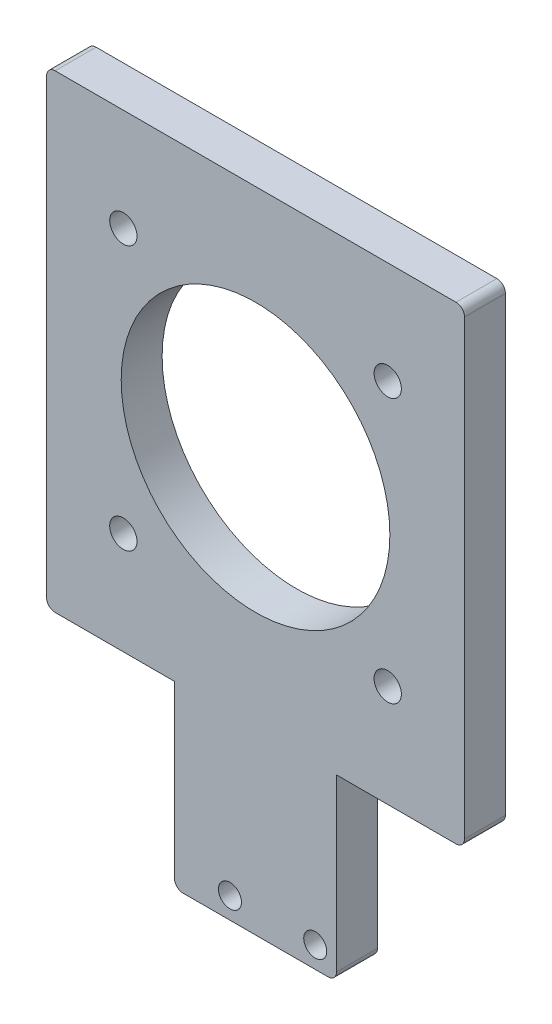
SolidWorks part; units mm, degrees
ref_plane "Plan de face" through (0, 0, 0) normal (0, 0, 1) x (1, 0, 0)
ref_plane "Plan de dessus" through (0, 0, 0) normal (0, 1, 0) x (1, 0, 0)
ref_plane "Plan de droite" through (0, 0, 0) normal (1, 0, 0) x (0, 0, -1)
ref_plane "Plan1" through (0, 0, 0) normal (0, 0, -1) x (-1, 0, 0)
sketch "Esquisse1" plane through (0, 0, 0) normal (0, 0, -1) x (-1, 0, 0)
  line L0 (-12.0004, 3.6502) -> (-12.0004, 56.6502)
  line L5 (-13.0004, 57.6502) -> (-60.0004, 57.6502)
  line L11 (-61.0004, 56.6502) -> (-61.0004, 3.6502)
  line L15 (-60.0004, 2.6502) -> (-46.0004, 2.6502)
  line L16 (-46.0004, 2.6502) -> (-46.0004, -17.3498)
  line L21 (-45.0004, -18.3498) -> (-28.0004, -18.3498)
  line L26 (-27.0004, -17.3498) -> (-27.0004, 2.6502)
  line L27 (-27.0004, 2.6502) -> (-13.0004, 2.6502)
  circle A0 centre (-36.5004, 30.1502) radius 15.75
  circle A1 centre (-52.0004, 14.6502) radius 1.6
  circle A2 centre (-52.0004, 45.6502) radius 1.6
  circle A3 centre (-21.0004, 14.6502) radius 1.6
  circle A4 centre (-21.0004, 45.6502) radius 1.6
  arc A5 (-61.0004, 56.6502) -> (-60.0004, 57.6502) centre (-60.0004, 56.6502) cw
  arc A6 (-13.0004, 57.6502) -> (-12.0004, 56.6502) centre (-13.0004, 56.6502) cw
  arc A7 (-61.0004, 3.6502) -> (-60.0004, 2.6502) centre (-60.0004, 3.6502) ccw
  arc A8 (-46.0004, -17.3498) -> (-45.0004, -18.3498) centre (-45.0004, -17.3498) ccw
  arc A9 (-28.0004, -18.3498) -> (-27.0004, -17.3498) centre (-28.0004, -17.3498) ccw
  arc A10 (-13.0004, 2.6502) -> (-12.0004, 3.6502) centre (-13.0004, 3.6502) ccw
  circle A11 centre (-43.5004, -15.8498) radius 1.35
  circle A12 centre (-33.5004, -15.8498) radius 1.35
  dimension "D1" = 31.5
  dimension "D2" = 36.5004
  dimension "D3" = 30.1502
  dimension "D4" = 15.5
  dimension "D5" = 15.5
  dimension "D6" = 3.2
  dimension "D7" = 15.5
  dimension "D8" = 15.5
  dimension "D9" = 3.2
  dimension "D10" = 3.2
  dimension "D11" = 15.5
  dimension "D12" = 15.5
  dimension "D13" = 3.2
  dimension "D14" = 15.5
  dimension "D15" = 15.5
  dimension "D23" = 1
  dimension "D24" = 1
  dimension "D25" = 1
  dimension "D26" = 1
  dimension "D27" = 1
  dimension "D28" = 1
  dimension "D29" = 2.7
  dimension "D30" = 2.7
  dimension "D31" = 10
  dimension "D32" = 2.5
  dimension "D33" = 2.5
  dimension "D34" = 2.5
  dimension "D16" = 49
  dimension "D17" = 24.5
  dimension "D18" = 55
  dimension "D19" = 27.5
  dimension "D20" = 15
  dimension "D21" = 19
  dimension "D22" = 21
extrude "Boss.-Extru.1" add sketch "Esquisse1" against normal blind 4.8
